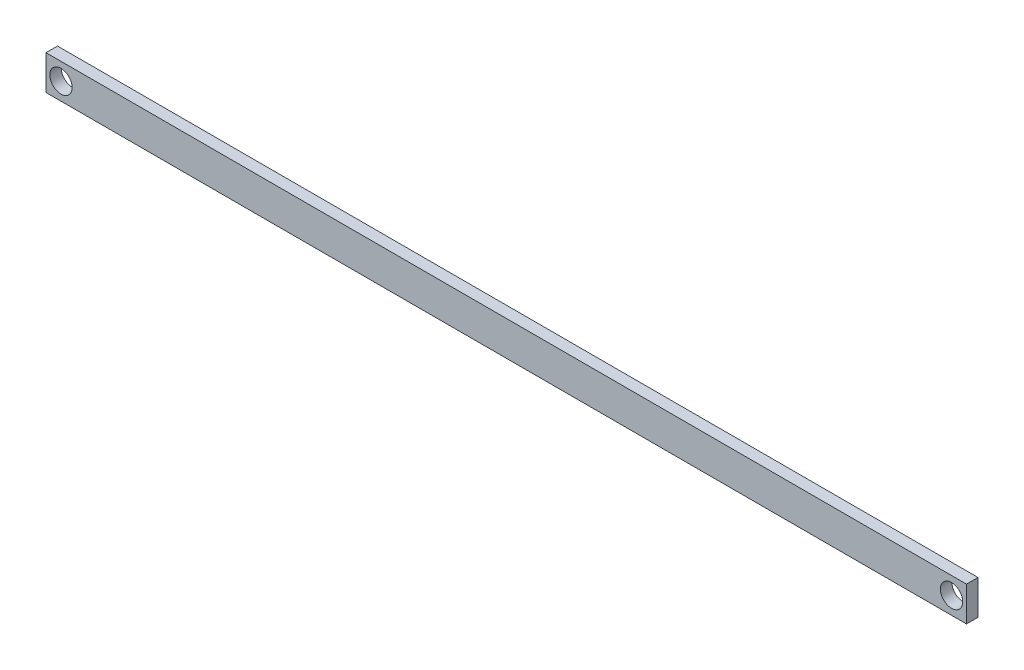
SolidWorks part; units mm, degrees
material "Plain Carbon Steel"
ref_plane "Front Plane" through (0, 0, 0) normal (0, 0, 1) x (1, 0, 0)
ref_plane "Top Plane" through (0, 0, 0) normal (0, 1, 0) x (1, 0, 0)
ref_plane "Right Plane" through (0, 0, 0) normal (1, 0, 0) x (0, 0, -1)
sketch "Sketch2" plane through (0, 0, 0) normal (0, 0, 1) x (1, 0, 0)
  line L0 (0, 0) -> (400, 0)
  line L1 (0, 0) -> (0, -15)
  line L2 (0, -15) -> (400, -15)
  line L3 (400, -15) -> (400, 0)
  dimension "D1" = 400
  dimension "D2" = 15
extrude "Boss-Extrude1" add sketch "Sketch2" against normal blind 5
sketch "Sketch3" plane through (0, 0, 0) normal (0, 0, 1) x (1, 0, 0)
  line L0 (0, 0) -> (0, -15) construction
  line L1 (400, -15) -> (400, 0) construction
  circle A0 centre (6.5, -7.5) radius 4.85
  circle A1 centre (393.5, -7.5) radius 4.85
  dimension "D1" = 9.7
  dimension "D3" = 9.7
  dimension "D2" = 6.5
  dimension "D4" = 6.5
extrude "Cut-Extrude1" cut sketch "Sketch3" against normal blind 5
